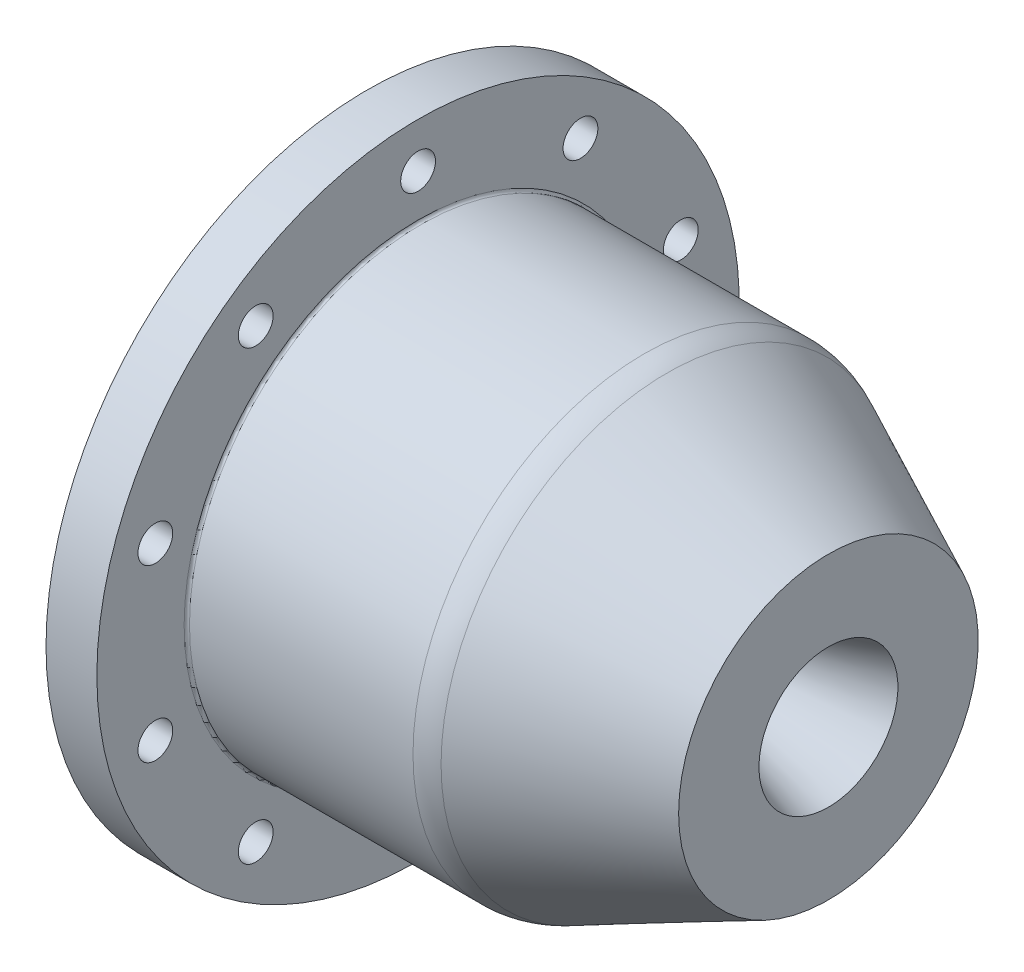
SolidWorks part; units mm, degrees
material "AISI 321 Annealed Stainless Steel (SS)"
ref_plane "Front Plane" through (0, 0, 0) normal (0, 0, 1) x (1, 0, 0)
ref_plane "Top Plane" through (0, 0, 0) normal (0, 1, 0) x (1, 0, 0)
ref_plane "Right Plane" through (0, 0, 0) normal (1, 0, 0) x (0, 0, -1)
sketch "Cross_section" plane through (0, 0, 0) normal (0, 0, 1) x (1, 0, 0)
  line L0 (0, 0) -> (509.0996, 165.4165) construction
  line L1 (0, 0) -> (343.611, 0) construction
  line L2 (21.0329, 6.834) -> (21.0329, 0) construction
  line L3 (21.0329, 6.834) -> (39.9422, 12.978)
  line L4 (39.9422, 12.978) -> (39.9422, 0) construction
  line L5 (0, 60) -> (0, 25) construction
  line L7 (21.0329, 6.834) -> (61.9245, 6.834) construction
  line L8 (0, 25) -> (-46.7, 25)
  line L9 (-46.7, 60) -> (-36.7, 60) construction
  line L10 (39.9422, 27.978) -> (39.9422, 12.978)
  line L11 (-46.2, 31) -> (-46.7, 31)
  line L12 (-36.7, 60) -> (-46.2, 60)
  line L13 (0, 25) -> (-36.698, 25) construction
  line L14 (0, 60) -> (0, 25) construction
  line L15 (-46.2, 60) -> (-46.2, 31)
  line L16 (-46.7, 60) -> (0, 60) construction
  line L17 (-36.7, 60) -> (-36.7, 43.2)
  line L18 (-36.7, 43.2) -> (7.7966, 43.2)
  line L19 (7.7942, 20.5) -> (0, 16) construction
  line L20 (21.0329, 15.834) -> (13.2387, 11.334) construction
  line L21 (7.7942, 20.5) -> (13.2387, 11.334)
  line L22 (7.7966, 43.2) -> (39.9422, 27.978)
  line L23 (-46.7, 31) -> (-46.7, 25)
  arc A0 (0, 25) -> (7.7942, 20.5) centre (0, 16) cw
  arc A1 (21.0329, 6.834) -> (13.2387, 11.334) centre (21.0329, 15.834) cw
  point P7 (39.9422, 0)
  point P14 (-23.35, 25)
  dimension "D8" = 9
  dimension "D7" = 9
  dimension "divergence_halfangle" = 18
  dimension "exit_radius" = 12.978
  dimension "throat_radius" = 6.834
  dimension "grain_outer_radius" = 25
  dimension "D1" = 46.7
  dimension "D4" = 15
  dimension "D5" = 16.8
  dimension "D6" = 10
  dimension "D9" = 60
  dimension "D10" = 60
  dimension "D2" = 0.5
  dimension "D3" = 6
revolve "Revolve" add sketch "Cross_section" angle 360 about L1
sketch "holes" plane through (-46.2, 0, 0) normal (-1, 0, 0) x (0, 0, 1)
  circle A0 centre (0, 51.6) radius 3.25
  circle A1 centre (30.3297, 41.7453) radius 3.25
  circle A2 centre (49.0745, 15.9453) radius 3.25
  circle A3 centre (49.0745, -15.9453) radius 3.25
  circle A4 centre (30.3297, -41.7453) radius 3.25
  circle A5 centre (0, -51.6) radius 3.25
  circle A6 centre (-30.3297, -41.7453) radius 3.25
  circle A7 centre (-49.0745, -15.9453) radius 3.25
  circle A8 centre (0, 0) radius 51.6 construction
  circle A9 centre (-49.0745, 15.9453) radius 3.25
  circle A10 centre (-30.3297, 41.7453) radius 3.25
  point P20 (0, 0)
  dimension "bolts_diameter" = 6.5
  dimension "D1" = 51.6
  dimension "D2" = 10
extrude "Cut-Extrude2" cut sketch "holes" against normal through all
ref_plane "Probe plane" through (-23.35, 0, 0) normal (-1, 0, 0) x (0, 0, 1)
sketch "Probe_hole_axis" plane through (-23.35, 0, 0) normal (-1, 0, 0) x (0, 0, 1)
  line L0 (0, 0) -> (-24.3288, 58.735) construction
  line L1 (0, 0) -> (0, 165.4165) construction
  dimension "D1" = 22.5
ref_plane "hole_cut_plane" through (0, 0, 0) normal (0, -0.5878, 0.809) x (1, 0, 0)
sketch "Sketch9" plane through (0, 0, 0) normal (0, -0.5878, 0.809) x (1, 0, 0)
  circle A0 centre (-23.35, 0) radius 1.8
  dimension "D1" = 3.6
extrude "probe_hole" cut sketch "Sketch9" against normal blind 57
fillet "Fillet1" radius 10 1 edges at (7.7966, 0, 43.2)
sketch "Team engraving" plane through (39.9422, 0, 0) normal (1, 0, 0) x (0, 0, -1)
  circle A0 centre (-0.1177, 0) radius 20.3603 construction
  text T0 "Castelli Heslop Lees Moeys Trouton   - 2014/15 Team -  Allan" font "Century Gothic" height 3.175
fillet "Fillet2" radius 0.5 1 edges at (-36.7, 0, 43.2)
fillet "Fillet3" radius 1.2 1 edges at (21.0329, 0, 6.834)
equation "\"throat_radius\"= 6.834mm"
equation "\"exit_radius\"= 12.978mm"
equation "\"divergence_halfangle\"= 18deg"
equation "\"grain_outer_radius\"= 25mm"
equation "\"total_thickness_radius\"= 60mm"
equation "\"PCC_insert_thickness\"= 4.67cm"
equation "\"D1@Cross_section\"=\"PCC_insert_thickness\""
equation "\"D1@holes\" = \"total_thickness_radius\" - 8.4"
equation "\"bolts_diameter\"= 6.5mm"
